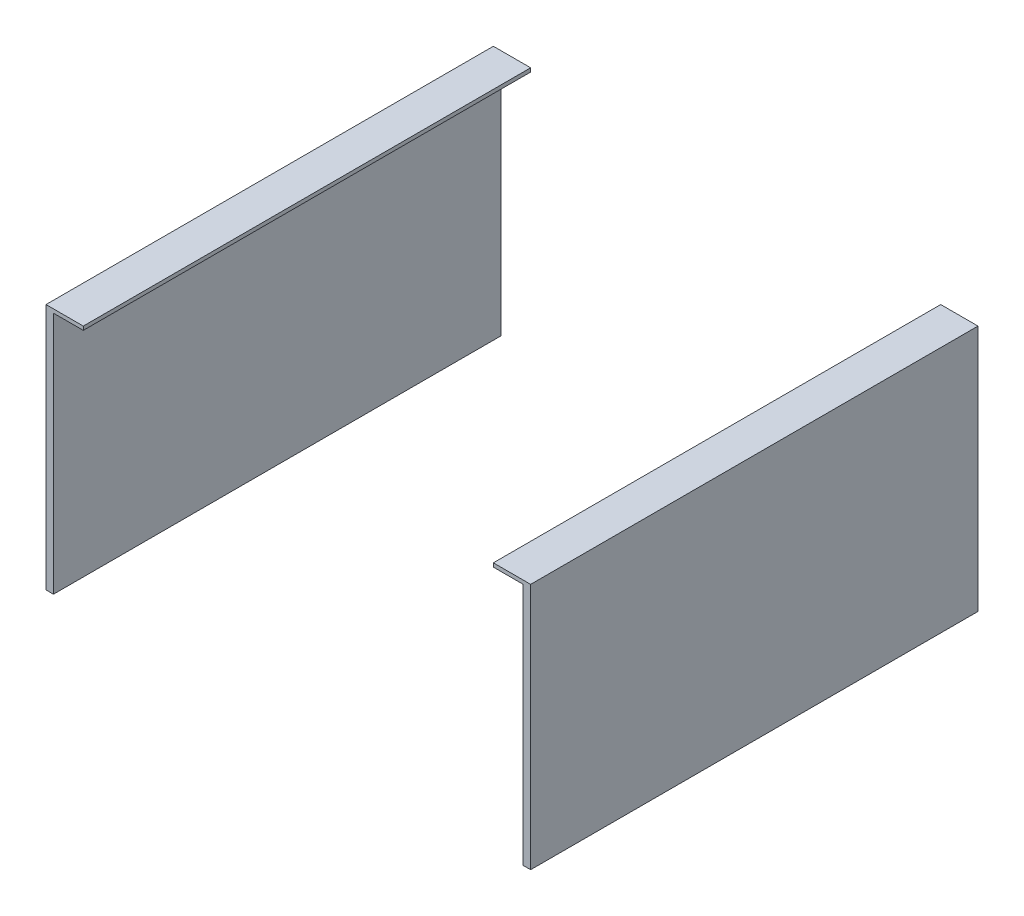
SolidWorks part; units mm, degrees
ref_plane "정면" through (0, 0, 0) normal (0, 0, 1) x (1, 0, 0)
ref_plane "윗면" through (0, 0, 0) normal (0, 1, 0) x (1, 0, 0)
ref_plane "우측면" through (0, 0, 0) normal (1, 0, 0) x (0, 0, -1)
sketch "스케치1" plane through (0, 0, 0) normal (0, 1, 0) x (1, 0, 0)
  line L1 (-65, -60) -> (65, -60)
  line L2 (-65, -60) -> (-65, 60)
  line L3 (-65, 60) -> (65, 60)
  line L4 (65, -60) -> (65, 60)
  line L5 (-65, -60) -> (65, 60) construction
  line L6 (-65, 60) -> (65, -60) construction
  point P0 (0, 0)
  dimension "D1" = 130
  dimension "D2" = 120
extrude "보스-돌출2" add sketch "스케치1" along normal blind 66.3
sketch "스케치3" plane through (0, 0, 60) normal (0, 0, 1) x (1, 0, 0)
  line L0 (-65, 0) -> (65, 0) construction
  line L1 (-63, 0) -> (63, 0)
  line L2 (-63, 0) -> (-63, 65.3)
  line L3 (-63, 65.3) -> (63, 65.3)
  line L4 (63, 0) -> (63, 65.3)
  line L5 (-65, 66.3) -> (-65, 0) construction
  line L6 (65, 66.3) -> (65, 0) construction
  line L7 (-65, 66.3) -> (65, 66.3) construction
  dimension "D1" = 2
  dimension "D2" = 2
  dimension "D3" = 1
extrude "컷-돌출1" cut sketch "스케치3" against normal blind 136.3
sketch "스케치4" plane through (0, 66.3, 0) normal (0, 1, 0) x (1, 0, 0)
  line L0 (65, 60) -> (-65, 60) construction
  line L1 (-55, 60) -> (55, 60)
  line L2 (-55, 60) -> (-55, -60)
  line L3 (-55, -60) -> (55, -60)
  line L4 (55, 60) -> (55, -60)
  line L5 (-65, -60) -> (65, -60) construction
  line L6 (-65, 60) -> (-65, -60) construction
  line L7 (65, -60) -> (65, 60) construction
  dimension "D1" = 10
  dimension "D2" = 10
extrude "컷-돌출2" cut sketch "스케치4" against normal blind 136.3
